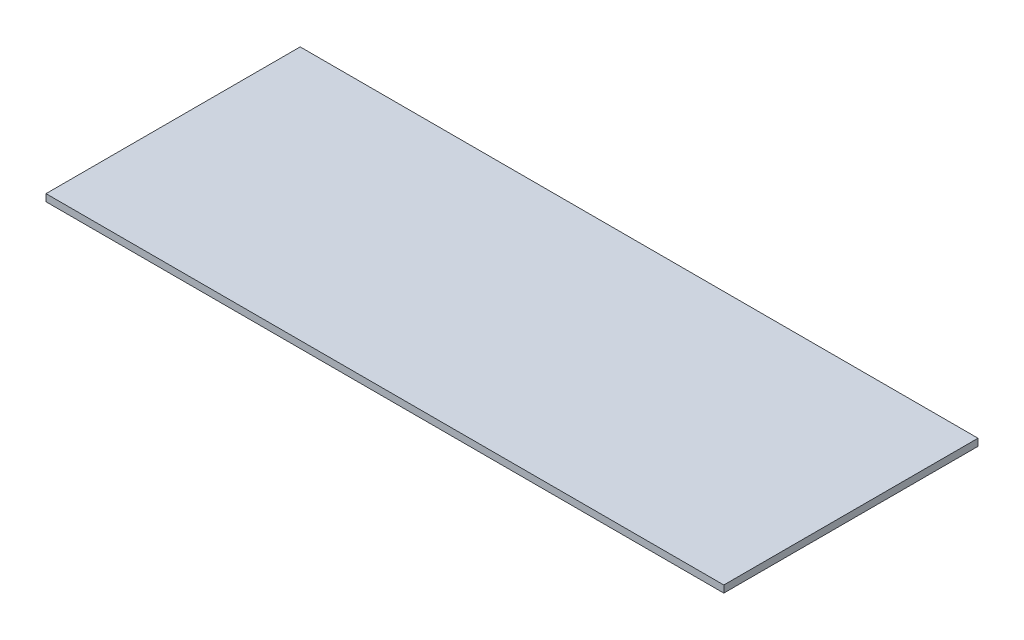
SolidWorks part; units mm, degrees
ref_plane "Front Plane" through (0, 0, 0) normal (0, 0, 1) x (1, 0, 0)
ref_plane "Top Plane" through (0, 0, 0) normal (0, 1, 0) x (1, 0, 0)
ref_plane "Right Plane" through (0, 0, 0) normal (1, 0, 0) x (0, 0, -1)
sketch "Sketch1" plane through (0, 0, 0) normal (0, 1, 0) x (1, 0, 0)
  line L1 (-304.8, -114.3) -> (304.8, -114.3)
  line L2 (-304.8, -114.3) -> (-304.8, 114.3)
  line L3 (-304.8, 114.3) -> (304.8, 114.3)
  line L4 (304.8, -114.3) -> (304.8, 114.3)
  line L5 (-304.8, -114.3) -> (304.8, 114.3) construction
  line L6 (-304.8, 114.3) -> (304.8, -114.3) construction
  point P0 (0, 0)
  dimension "D1" = 609.6
  dimension "D2" = 228.6
extrude "Boss-Extrude1" add sketch "Sketch1" along normal blind 6.35
